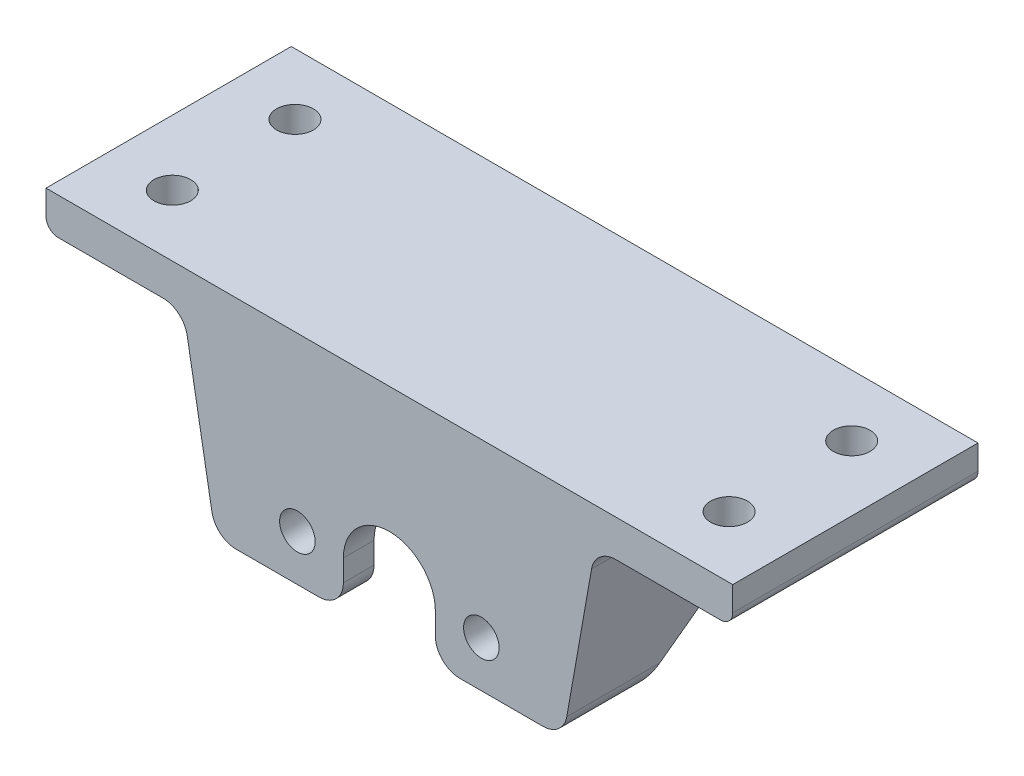
SolidWorks part; units mm, degrees
ref_plane "Front Plane" through (0, 0, 0) normal (0, 0, 1) x (1, 0, 0)
ref_plane "Top Plane" through (0, 0, 0) normal (0, 1, 0) x (1, 0, 0)
ref_plane "Right Plane" through (0, 0, 0) normal (1, 0, 0) x (0, 0, -1)
sketch "Motor Profile" plane through (0, 0, 0) normal (0, 0, 1) x (1, 0, 0)
  circle A0 centre (0, 0) radius 10 construction
  circle A1 centre (-7.5, 0) radius 1 construction
  circle A2 centre (7.5, 0) radius 1 construction
  circle A3 centre (0, 0) radius 3.5 construction
  dimension "D1" = 7
  dimension "D2" = 2
  dimension "D3" = 20
  dimension "D4" = 2
  dimension "D5" = 15
  dimension "D6" = 7.5
sketch "Sketch2" plane through (0, 0, 0) normal (0, 0, 1) x (1, 0, 0)
  line L0 (-3.75, 0) -> (-3.75, -1.75)
  line L1 (3.75, 0) -> (3.75, -1.75)
  line L2 (-5.75, -3.75) -> (-12.5, -3.75)
  line L3 (-14.4696, -2.0973) -> (-16.4876, 9.3473)
  line L4 (5.75, -3.75) -> (12.5, -3.75)
  line L5 (14.4696, -2.0973) -> (16.4876, 9.3473)
  line L7 (-18.4572, 11) -> (-27, 11)
  line L8 (18.4572, 11) -> (27, 11)
  line L9 (-28, 12) -> (-28, 14)
  line L10 (-28, 14) -> (28, 14)
  line L11 (28, 14) -> (28, 12)
  arc A0 (3.75, 0) -> (-3.75, 0) centre (0, 0) ccw
  circle A1 centre (-7.5, 0) radius 1.45
  circle A2 centre (7.5, 0) radius 1.45
  arc A3 (-5.75, -3.75) -> (-3.75, -1.75) centre (-5.75, -1.75) ccw
  arc A4 (5.75, -3.75) -> (3.75, -1.75) centre (5.75, -1.75) cw
  arc A5 (-12.5, -3.75) -> (-14.4696, -2.0973) centre (-12.5, -1.75) cw
  arc A6 (14.4696, -2.0973) -> (12.5, -3.75) centre (12.5, -1.75) cw
  arc A8 (-16.4876, 9.3473) -> (-18.4572, 11) centre (-18.4572, 9) ccw
  arc A9 (16.4876, 9.3473) -> (18.4572, 11) centre (18.4572, 9) cw
  arc A10 (-27, 11) -> (-28, 12) centre (-27, 12) cw
  arc A11 (28, 12) -> (27, 11) centre (27, 12) cw
  point P20 (-3.75, -3.75)
  point P23 (3.75, -3.75)
  point P27 (-14.1782, -3.75)
  point P33 (-16.779, 11)
  point P36 (16.779, 11)
  point P39 (-28, 11)
  dimension "D1" = 7.5
  dimension "D2" = 2.9
  dimension "D7" = 2
  dimension "D8" = 2
  dimension "D9" = 2
  dimension "D10" = 2
  dimension "D13" = 2
  dimension "D14" = 2
  dimension "D16" = 1
  dimension "D17" = 1
  dimension "D4" = 3.75
  dimension "D3" = 80
  dimension "D5" = 80
  dimension "D6" = 5
  dimension "D11" = 11
  dimension "D12" = 3
  dimension "D15" = 56
extrude "Boss-Extrude1" add sketch "Sketch2" against normal blind 2.5
ref_plane "Plane2" through (0, 0, -20) normal (0, 0, 1) x (1, 0, 0)
sketch "Sketch3" plane through (0, 0, -2.5) normal (0, 0, -1) x (-1, 0, 0)
  line L11 (-11, -2.75) -> (-11, 6)
  line L12 (-5.75, -3.75) -> (-12.5, -3.75) construction
  line L13 (-6, 11) -> (6, 11)
  line L14 (11, 6) -> (11, -2.75)
  line L15 (12.5, -3.75) -> (5.75, -3.75) construction
  line L16 (12, -3.75) -> (12.5, -3.75)
  line L17 (-12, -3.75) -> (-12.5, -3.75)
  line L22 (3.75, 0) -> (3.75, -1.75)
  line L23 (5.75, -3.75) -> (12.5, -3.75)
  line L24 (14.4696, -2.0973) -> (16.4876, 9.3473)
  line L25 (18.4572, 11) -> (27, 11)
  line L26 (28, 12) -> (28, 14)
  line L27 (28, 14) -> (-28, 14)
  line L28 (-28, 14) -> (-28, 12)
  line L29 (-27, 11) -> (-18.4572, 11)
  line L30 (-16.4876, 9.3473) -> (-14.4696, -2.0973)
  line L31 (-12.5, -3.75) -> (-5.75, -3.75)
  line L32 (-3.75, -1.75) -> (-3.75, 0)
  line L35 (14.4696, -2.0973) -> (16.4876, 9.3473)
  line L36 (18.4572, 11) -> (27, 11)
  line L37 (28, 12) -> (28, 14)
  line L38 (28, 14) -> (-28, 14)
  line L39 (-28, 14) -> (-28, 12)
  line L40 (-27, 11) -> (-18.4572, 11)
  line L41 (-16.4876, 9.3473) -> (-14.4696, -2.0973)
  arc A9 (-11, 6) -> (-6, 11) centre (-6, 6) cw
  arc A10 (11, 6) -> (6, 11) centre (6, 6) ccw
  arc A11 (-11, -2.75) -> (-12, -3.75) centre (-12, -2.75) cw
  arc A12 (12, -3.75) -> (11, -2.75) centre (12, -2.75) cw
  arc A18 (3.75, 0) -> (-3.75, 0) centre (0, 0) ccw
  arc A19 (3.75, -1.75) -> (5.75, -3.75) centre (5.75, -1.75) ccw
  arc A20 (12.5, -3.75) -> (14.4696, -2.0973) centre (12.5, -1.75) ccw
  arc A21 (18.4572, 11) -> (16.4876, 9.3473) centre (18.4572, 9) ccw
  arc A22 (27, 11) -> (28, 12) centre (27, 12) ccw
  arc A23 (-28, 12) -> (-27, 11) centre (-27, 12) ccw
  arc A24 (-16.4876, 9.3473) -> (-18.4572, 11) centre (-18.4572, 9) ccw
  arc A25 (-14.4696, -2.0973) -> (-12.5, -3.75) centre (-12.5, -1.75) ccw
  arc A26 (-5.75, -3.75) -> (-3.75, -1.75) centre (-5.75, -1.75) ccw
  arc A29 (12.5, -3.75) -> (14.4696, -2.0973) centre (12.5, -1.75) ccw
  arc A30 (18.4572, 11) -> (16.4876, 9.3473) centre (18.4572, 9) ccw
  arc A31 (27, 11) -> (28, 12) centre (27, 12) ccw
  arc A32 (-28, 12) -> (-27, 11) centre (-27, 12) ccw
  arc A33 (-16.4876, 9.3473) -> (-18.4572, 11) centre (-18.4572, 9) ccw
  arc A34 (-14.4696, -2.0973) -> (-12.5, -3.75) centre (-12.5, -1.75) ccw
  point P7 (0, 11)
  point P26 (-11, -3.75)
  point P29 (11, -3.75)
  dimension "D3" = 5
  dimension "D4" = 5
  dimension "D5" = 1
  dimension "D6" = 1
  dimension "D2" = 11
  dimension "D1" = 0
extrude "Boss-Extrude2" add sketch "Sketch3" along direction (0, 0, 1) on the side of the normal up to surface (17.5 mm away) up to plane "Plane2"
sketch "Sketch6" plane through (0, 0, 0) normal (1, 0, 0) x (0, 0, -1)
  line L0 (6, -3.75) -> (20, 11)
  line L1 (20, -3.75) -> (0, -3.75) construction
  line L2 (20, 9.7625) -> (20, -9.7625) construction
  line L3 (20, 11) -> (0, 11) construction
  line L4 (6, -3.75) -> (20, -3.75)
  line L5 (20, -3.75) -> (20, 11)
  dimension "D1" = 6
extrude "Cut-Extrude1" cut sketch "Sketch6" against normal through all both and the other way through all
sketch "Sketch9" plane through (0, 11, 0) normal (0, -1, 0) x (1, 0, 0)
  line L0 (18.4572, -20) -> (27, -20) construction
  line L1 (28, -20) -> (28, 0) construction
  line L3 (18.4572, 0) -> (27, 0) construction
  circle A0 centre (22.7, -15) radius 1.5
  circle A1 centre (22.7, -5) radius 1.5
  dimension "D1" = 3
  dimension "D2" = 5
  dimension "D3" = 5
  dimension "D4" = 5.3
extrude "Cut-Extrude2" cut sketch "Sketch9" against normal through all
mirror "Mirror1" about plane through (0, 0, 0) normal (1, 0, 0) of "Cut-Extrude2"
equation "\"D6@Motor Profile\" = \"D5@Motor Profile\" / 2"
equation "\"D5@Sketch2\"=\"D3@Sketch2\""
